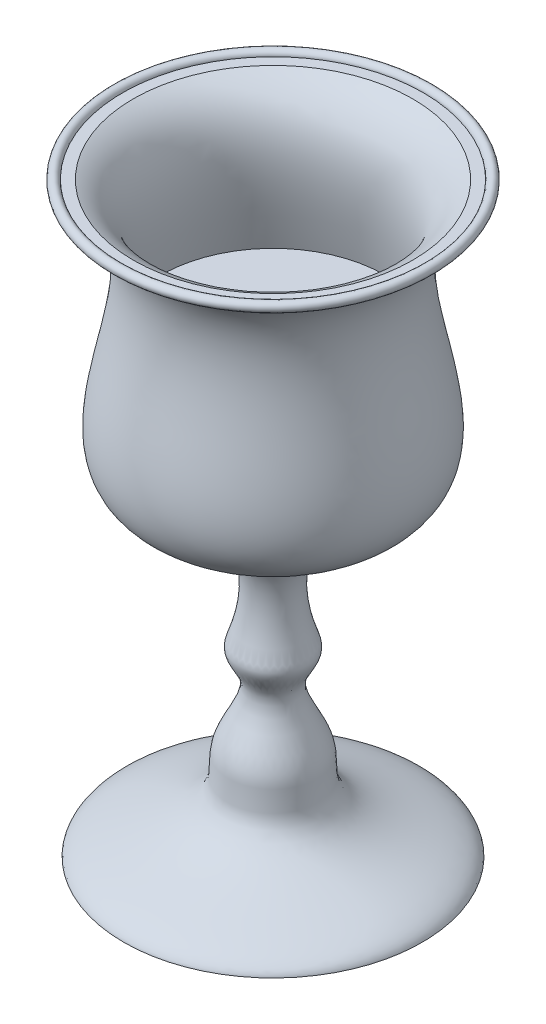
SolidWorks part; units mm, degrees
ref_plane "Front Plane" through (0, 0, 0) normal (0, 0, 1) x (1, 0, 0)
ref_plane "Top Plane" through (0, 0, 0) normal (0, 1, 0) x (1, 0, 0)
ref_plane "Right Plane" through (0, 0, 0) normal (1, 0, 0) x (0, 0, -1)
sketch "Sketch1" plane through (0, 0, 0) normal (0, 0, 1) x (1, 0, 0)
  line L0 (0, 0) -> (40.9402, 0)
  line L1 (0, 0) -> (0, 80.413)
  line L2 (38.3491, 160.8259) -> (42.5821, 160.8259)
  spline S0 degree 3 poles (40.9402, 0) (39.592, 5.604) (9.921, 8.0974) (13.7218, 29.4918) (3.3437, 39.3389) (8.5071, 46.5325) (9.8376, 49.7647) (6.3257, 58.8498) (4.0131, 80.5496) (60.1534, 89.1818) (15.5876, 145.5406) (42.5821, 160.8259) knots 0 0 0 0 0.173163 0.216359 0.311104 0.331403 0.347583 0.362384 0.478387 0.619446 1 1 1 1
  spline S1 degree 3 poles (0, 80.413) (21.8881, 84.736) (48.7681, 95.2005) (16.4899, 150.451) (38.3491, 160.8259) knots 0 0 0 0 0.287217 1 1 1 1
revolve "Revolve1" add sketch "Sketch1" angle 360 about L1
sketch "Sketch2" plane through (0, 0, 0) normal (0, 0, 1) x (1, 0, 0)
  line L0 (0, 114.1934) -> (0, 143.3678) construction
  circle A0 centre (42.5821, 160.8259) radius 1.3258
revolve "Revolve2" add sketch "Sketch2" angle 360 about L0
sketch "Sketch6" plane through (0, 0, 0) normal (0, 0, 1) x (1, 0, 0)
  line L0 (0, 80.5012) -> (0, 122.673)
  line L1 (0, 122.673) -> (30.8203, 122.673)
  spline S0 degree 3 poles (0, 80.5012) (20.7096, 84.6624) (37.2983, 90.839) (32.9895, 111.7413) (30.8203, 122.673) knots 0.006862 0.006862 0.006862 0.006862 0.287217 0.580272 0.580272 0.580272 0.580272
revolve "Revolve3" add sketch "Sketch6" angle 360 about L0
